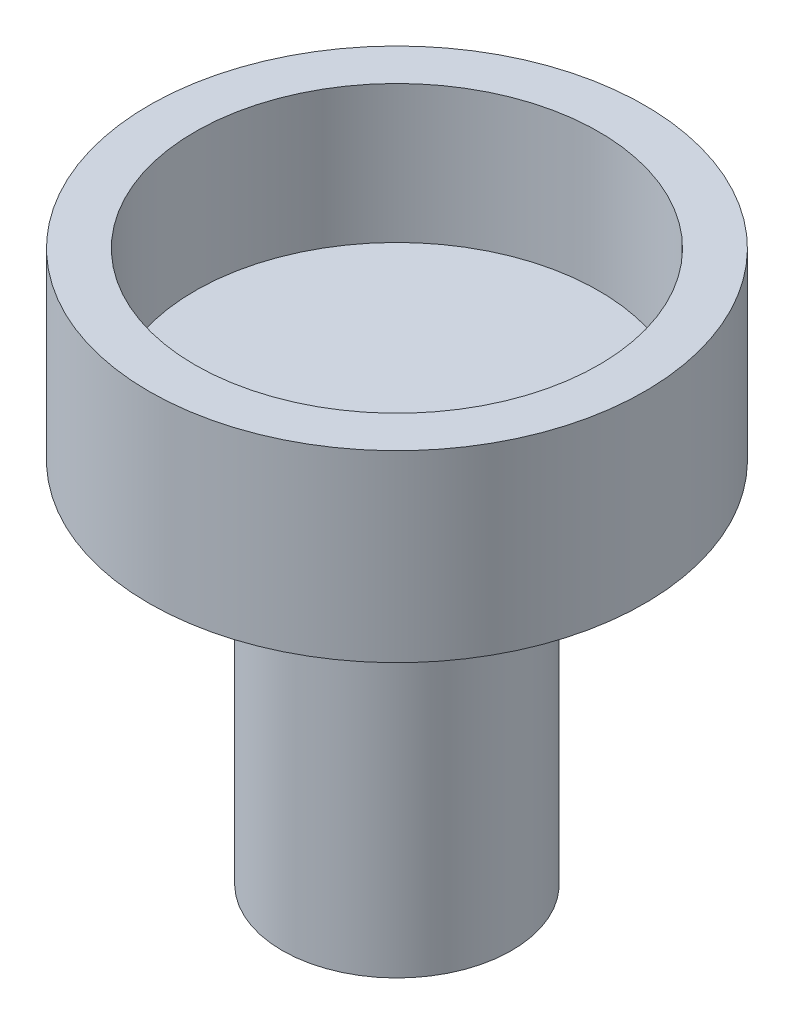
SolidWorks part; units mm, degrees
material "Natural Rubber"
ref_plane "Front Plane" through (0, 0, 0) normal (0, 0, 1) x (1, 0, 0)
ref_plane "Top Plane" through (0, 0, 0) normal (0, 1, 0) x (1, 0, 0)
ref_plane "Right Plane" through (0, 0, 0) normal (1, 0, 0) x (0, 0, -1)
sketch "BottomBaseS" plane through (0, 0, 0) normal (0, 1, 0) x (1, 0, 0)
  circle A0 centre (0, 0) radius 1.25
  dimension "D1" = 2.5
extrude "BOTTOM BASE" add sketch "BottomBaseS" against normal blind 4
sketch "MainBaseS" plane through (0, 0, 0) normal (0, 1, 0) x (1, 0, 0)
  circle A0 centre (0, 0) radius 2.7
  circle A1 centre (0, 0) radius 1.25 construction
  dimension "D1" = 1.45
  dimension "D2" = 5.4
extrude "MAIN BASE" add sketch "MainBaseS" along normal blind 0.5
sketch "WallS" plane through (0, 0.5, 0) normal (0, 1, 0) x (1, 0, 0)
  circle A0 centre (0, 0) radius 2.7
  circle A1 centre (0, 0) radius 2.2
  circle A2 centre (0, 0) radius 2.7 construction
  dimension "D1" = 0.5
extrude "WALL" add sketch "WallS" along normal offset from surface (1.5 mm away) 2 up to face at (0, 0, 1.25)
